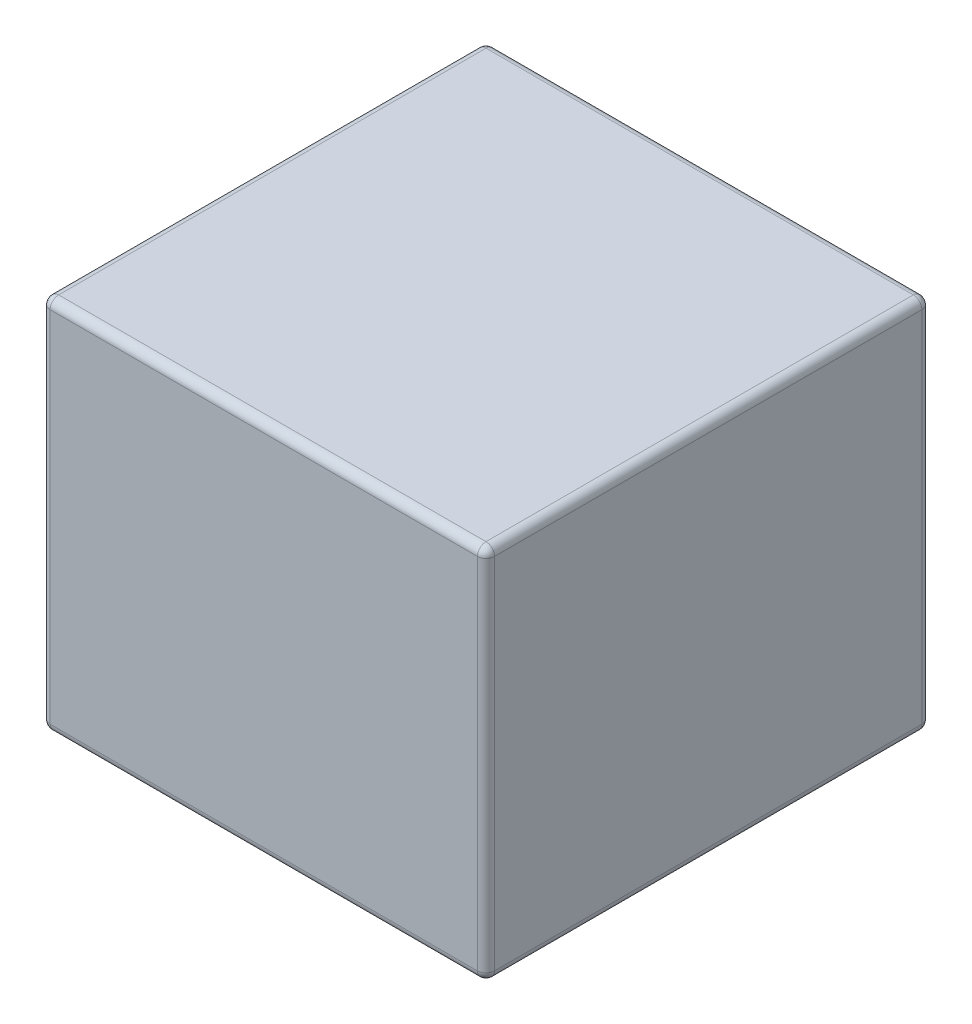
SolidWorks part; units mm, degrees
material "Nylon 101"
ref_plane "Front Plane" through (0, 0, 0) normal (0, 0, 1) x (1, 0, 0)
ref_plane "Top Plane" through (0, 0, 0) normal (0, 1, 0) x (1, 0, 0)
ref_plane "Right Plane" through (0, 0, 0) normal (1, 0, 0) x (0, 0, -1)
sketch "Sketch1" plane through (0, 0, 0) normal (0, 1, 0) x (1, 0, 0)
  line L1 (-165.1, -165.1) -> (165.1, -165.1)
  line L2 (-165.1, -165.1) -> (-165.1, 165.1)
  line L3 (-165.1, 165.1) -> (165.1, 165.1)
  line L4 (165.1, -165.1) -> (165.1, 165.1)
  line L5 (-165.1, -165.1) -> (165.1, 165.1) construction
  line L6 (-165.1, 165.1) -> (165.1, -165.1) construction
  point P0 (0, 0)
  dimension "D1" = 330.2
  dimension "D2" = 330.2
extrude "Boss-Extrude1" add sketch "Sketch1" along normal blind 279.4
fillet "Fillet1" radius 6.35 12 edges at (165.1, 0, 0) (0, 0, -165.1) (-165.1, 0, 0) (0, 0, 165.1) (165.1, 279.4, 0) (0, 279.4, -165.1) (-165.1, 279.4, 0) (165.1, 139.7, 165.1) (-165.1, 139.7, 165.1) (-165.1, 139.7, -165.1) (165.1, 139.7, -165.1) (0, 279.4, 165.1)
